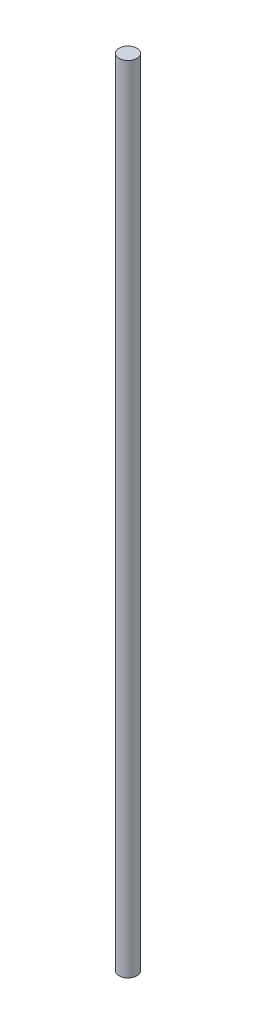
SolidWorks part; units mm, degrees
ref_plane "Front Plane" through (0, 0, 0) normal (0, 0, 1) x (1, 0, 0)
ref_plane "Top Plane" through (0, 0, 0) normal (0, 1, 0) x (1, 0, 0)
ref_plane "Right Plane" through (0, 0, 0) normal (1, 0, 0) x (0, 0, -1)
sketch "Sketch1" plane through (0, 0, 0) normal (0, 1, 0) x (1, 0, 0)
  circle A0 centre (0, 0) radius 6
  dimension "D1" = 12
extrude "Boss-Extrude1" add sketch "Sketch1" along normal blind 536
cosmetic thread "Cosmetic Thread5" parameters "D1"=5, "D2"=11
cosmetic thread "Cosmetic Thread6" parameters "D1"=44.5, "D2"=11
cosmetic thread "Cosmetic Thread7" parameters "D1"=44.5, "D2"=11
